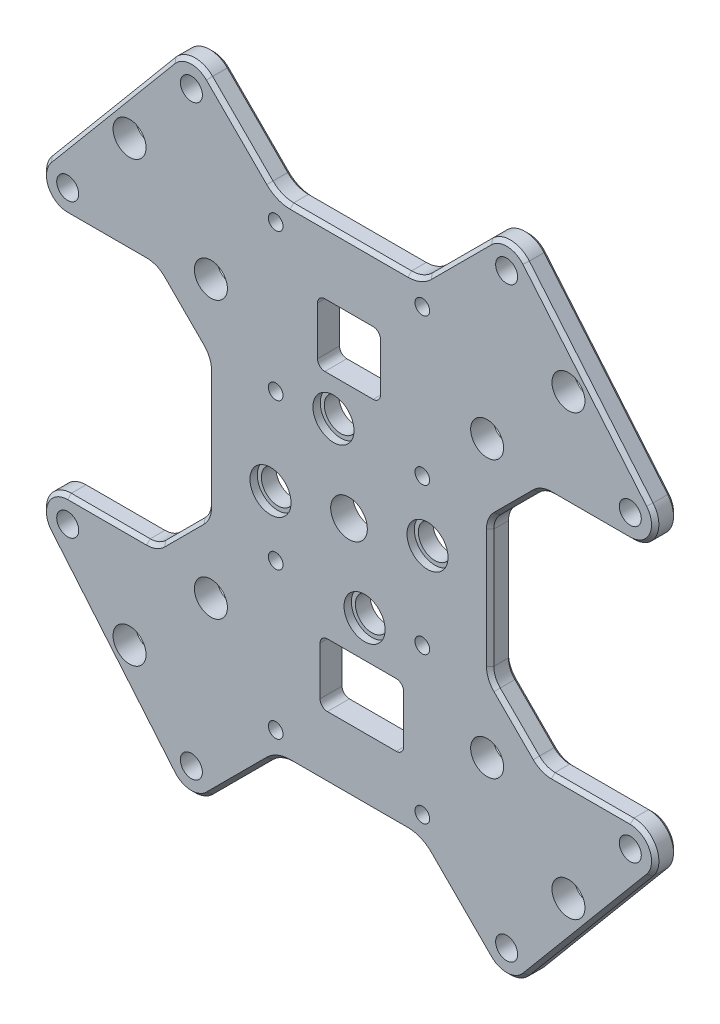
SolidWorks part; units mm, degrees
ref_plane "前视基准面" through (0, 0, 0) normal (0, 0, 1) x (1, 0, 0)
ref_plane "上视基准面" through (0, 0, 0) normal (0, 1, 0) x (1, 0, 0)
ref_plane "右视基准面" through (0, 0, 0) normal (1, 0, 0) x (0, 0, -1)
sketch "草图1" plane through (0, 0, 0) normal (0, 0, 1) x (1, 0, 0)
  line L0 (0, 0) -> (0, -25.4464) construction
  line L1 (0, 0) -> (25.4542, 0) construction
  line L22 (-19.0958, 42.4042) -> (-10.8632, 34.1716)
  line L23 (1.75, -20) -> (0, -20) construction
  line L24 (-14.5, -7) -> (18, -7) construction
  line L26 (-3.2929, 24.2929) -> (3.2929, 24.2929)
  line L27 (-4.2929, 23.2929) -> (-4.2929, 16.7071)
  line L28 (-15.25, 0.5) -> (15.25, 0.5) construction
  line L29 (-17.25, 2.5) -> (-17.25, 37.5) construction
  line L30 (-15.25, 39.5) -> (15.25, 39.5) construction
  line L31 (17.25, 2.5) -> (17.25, 37.5) construction
  line L32 (-15.5, -8) -> (-15.5, -32) construction
  line L33 (-17.25, 0.5) -> (17.25, 39.5) construction
  line L34 (-17.25, 39.5) -> (17.25, 0.5) construction
  line L35 (-10, 30) -> (10, 30) construction
  line L36 (-10, 30) -> (-10, 10) construction
  line L37 (-10, 10) -> (10, 10) construction
  line L38 (10, 30) -> (10, 10) construction
  line L39 (-10, 30) -> (10, 10) construction
  line L40 (-10, 10) -> (10, 30) construction
  line L41 (-8.0348, 33) -> (8.0348, 33)
  line L42 (-45.823, 52.8941) -> (-16.201, 23.2721) construction
  line L43 (-3.2929, 15.7071) -> (3.2929, 15.7071)
  line L44 (-14.5, -33) -> (18, -33) construction
  line L45 (19, -8) -> (19, -32) construction
  line L46 (-15.5, -7) -> (19, -33) construction
  line L47 (-15.5, -33) -> (19, -7) construction
  line L48 (-10, -30) -> (10, -30) construction
  line L49 (-10, -30) -> (-10, -10) construction
  line L50 (-10, -10) -> (10, -10) construction
  line L51 (10, -30) -> (10, -10) construction
  line L52 (-10, -30) -> (10, -10) construction
  line L53 (-10, -10) -> (10, -30) construction
  line L54 (-24.1062, 42.1835) -> (-40.9735, 22.0509)
  line L55 (-38.3673, 16.4673) -> (-27.6095, 16.4673)
  line L56 (-25.4882, 15.5887) -> (-20.1287, 10.2292)
  line L57 (-19.25, 8.1079) -> (-19.25, -8.1079)
  line L58 (-71.0072, 63.9361) -> (-82.5161, 75.445) construction
  line L59 (19.25, 8.1079) -> (19.25, -8.1079)
  line L60 (25.4882, 15.5887) -> (20.1287, 10.2292)
  line L61 (38.3673, 16.4673) -> (27.6095, 16.4673)
  line L62 (24.1062, 42.1835) -> (40.9735, 22.0509)
  line L63 (19.0958, 42.4042) -> (10.8632, 34.1716)
  line L64 (25.4882, -15.5887) -> (20.1287, -10.2292)
  line L65 (38.3673, -16.4673) -> (27.6095, -16.4673)
  line L66 (24.1062, -42.1835) -> (40.9735, -22.0509)
  line L67 (19.0958, -42.4042) -> (10.8632, -34.1716)
  line L68 (-8.0348, -33) -> (8.0348, -33)
  line L69 (-19.0958, -42.4042) -> (-10.8632, -34.1716)
  line L70 (-24.1062, -42.1835) -> (-40.9735, -22.0509)
  line L71 (-38.3673, -16.4673) -> (-27.6095, -16.4673)
  line L72 (-25.4882, -15.5887) -> (-20.1287, -10.2292)
  line L73 (4.2929, 23.2929) -> (4.2929, 16.7071)
  line L74 (-4.2929, 24.2929) -> (4.2929, 15.7071) construction
  line L75 (-4.2929, 15.7071) -> (4.2929, 24.2929) construction
  line L76 (-2.9463, -15.7071) -> (6.4463, -15.7071)
  line L77 (-3.9463, -16.7071) -> (-3.9463, -23.2929)
  line L78 (-2.9463, -24.2929) -> (6.4463, -24.2929)
  line L79 (7.4463, -16.7071) -> (7.4463, -23.2929)
  line L80 (-3.9463, -15.7071) -> (7.4463, -24.2929) construction
  line L81 (-3.9463, -24.2929) -> (7.4463, -15.7071) construction
  circle A4 centre (10, -10) radius 1 construction
  circle A5 centre (10, 10) radius 1 construction
  circle A6 centre (-10, 10) radius 1 construction
  arc A7 (-3.9463, -23.2929) -> (-2.9463, -24.2929) centre (-2.9463, -23.2929) ccw
  circle A8 centre (-10, -10) radius 1 construction
  arc A9 (6.4463, -24.2929) -> (7.4463, -23.2929) centre (6.4463, -23.2929) ccw
  arc A10 (-2.9463, -15.7071) -> (-3.9463, -16.7071) centre (-2.9463, -16.7071) ccw
  arc A11 (6.4463, -15.7071) -> (7.4463, -16.7071) centre (6.4463, -16.7071) cw
  circle A16 centre (10, -10) radius 1
  circle A17 centre (10, 10) radius 1
  circle A18 centre (-10, 10) radius 1
  circle A20 centre (-10, -10) radius 1
  arc A24 (-4.2929, 16.7071) -> (-3.2929, 15.7071) centre (-3.2929, 16.7071) ccw
  arc A25 (3.2929, 15.7071) -> (4.2929, 16.7071) centre (3.2929, 16.7071) ccw
  arc A26 (3.2929, 24.2929) -> (4.2929, 23.2929) centre (3.2929, 23.2929) cw
  arc A27 (-3.2929, 24.2929) -> (-4.2929, 23.2929) centre (-3.2929, 23.2929) ccw
  circle A42 centre (0, 0) radius 2.5
  arc A58 (-17.25, 37.5) -> (-15.25, 39.5) centre (-15.25, 37.5) cw construction
  arc A59 (-15.25, 0.5) -> (-17.25, 2.5) centre (-15.25, 2.5) cw construction
  arc A60 (15.25, 0.5) -> (17.25, 2.5) centre (15.25, 2.5) ccw construction
  circle A61 centre (-10, 30) radius 1
  circle A62 centre (10, 30) radius 1
  arc A63 (-14.5, -7) -> (-15.5, -8) centre (-14.5, -8) ccw construction
  arc A64 (-15.5, -32) -> (-14.5, -33) centre (-14.5, -32) ccw construction
  arc A65 (18, -33) -> (19, -32) centre (18, -32) ccw construction
  arc A66 (18, -7) -> (19, -8) centre (18, -8) cw construction
  circle A67 centre (10, -30) radius 1
  circle A68 centre (-10, -30) radius 1
  arc A69 (15.25, 39.5) -> (17.25, 37.5) centre (15.25, 37.5) cw construction
  circle A70 centre (-38.3673, -19.8673) radius 1.5 construction
  circle A71 centre (-29.9337, -29.9337) radius 1.5 construction
  circle A72 centre (-21.5, -40) radius 1.5 construction
  circle A73 centre (-38.3673, -19.8673) radius 1.5
  circle A74 centre (-29.9337, -29.9337) radius 1.5
  circle A75 centre (-21.5, -40) radius 1.5
  circle A80 centre (-10.7071, -2.1213) radius 1.5 construction
  circle A81 centre (2.1213, -10.7071) radius 1.5 construction
  circle A82 centre (10.7071, 2.1213) radius 1.5 construction
  circle A83 centre (-2.1213, 10.7071) radius 1.5 construction
  circle A84 centre (-29.9337, 29.9337) radius 1.5 construction
  circle A85 centre (-18.8388, 18.8388) radius 1.5 construction
  circle A86 centre (29.9337, 29.9337) radius 1.5 construction
  circle A87 centre (18.8388, 18.8388) radius 1.5 construction
  circle A88 centre (29.9337, -29.9337) radius 1.5 construction
  circle A89 centre (18.8388, -18.8388) radius 1.5 construction
  circle A90 centre (-18.8388, -18.8388) radius 1.5 construction
  circle A95 centre (-10.7071, -2.1213) radius 1.5
  circle A96 centre (2.1213, -10.7071) radius 1.5
  circle A97 centre (10.7071, 2.1213) radius 1.5
  circle A98 centre (-2.1213, 10.7071) radius 1.5
  circle A99 centre (-29.9337, 29.9337) radius 1.5
  circle A100 centre (-18.8388, 18.8388) radius 1.5
  circle A101 centre (29.9337, 29.9337) radius 1.5
  circle A102 centre (18.8388, 18.8388) radius 1.5
  circle A103 centre (29.9337, -29.9337) radius 1.5
  circle A104 centre (18.8388, -18.8388) radius 1.5
  circle A105 centre (-18.8388, -18.8388) radius 1.5
  circle A106 centre (-84.8528, -84.8528) radius 77.5 construction
  circle A107 centre (-21.5, 40) radius 1.5
  circle A108 centre (-29.9337, 29.9337) radius 1.5
  circle A109 centre (-38.3673, 19.8673) radius 1.5
  circle A110 centre (21.5, -40) radius 1.5
  circle A111 centre (29.9337, -29.9337) radius 1.5
  circle A112 centre (38.3673, -19.8673) radius 1.5
  circle A113 centre (38.3673, 19.8673) radius 1.5
  circle A114 centre (29.9337, 29.9337) radius 1.5
  circle A115 centre (21.5, 40) radius 1.5
  circle A116 centre (-21.5, 40) radius 3.4 construction
  circle A117 centre (-29.9337, 29.9337) radius 3.4 construction
  circle A118 centre (-38.3673, 19.8673) radius 3.4 construction
  arc A119 (-24.1062, 42.1835) -> (-19.0958, 42.4042) centre (-21.5, 40) cw
  arc A120 (-10.8632, 34.1716) -> (-8.0348, 33) centre (-8.0348, 37) ccw
  arc A121 (-40.9735, 22.0509) -> (-38.3673, 16.4673) centre (-38.3673, 19.8673) ccw
  arc A122 (-20.1287, 10.2292) -> (-19.25, 8.1079) centre (-22.25, 8.1079) cw
  arc A123 (-27.6095, 16.4673) -> (-25.4882, 15.5887) centre (-27.6095, 13.4673) cw
  arc A124 (20.1287, 10.2292) -> (19.25, 8.1079) centre (22.25, 8.1079) ccw
  arc A125 (27.6095, 16.4673) -> (25.4882, 15.5887) centre (27.6095, 13.4673) ccw
  arc A126 (40.9735, 22.0509) -> (38.3673, 16.4673) centre (38.3673, 19.8673) cw
  arc A127 (24.1062, 42.1835) -> (19.0958, 42.4042) centre (21.5, 40) ccw
  arc A128 (10.8632, 34.1716) -> (8.0348, 33) centre (8.0348, 37) cw
  arc A129 (20.1287, -10.2292) -> (19.25, -8.1079) centre (22.25, -8.1079) cw
  arc A130 (27.6095, -16.4673) -> (25.4882, -15.5887) centre (27.6095, -13.4673) cw
  arc A131 (40.9735, -22.0509) -> (38.3673, -16.4673) centre (38.3673, -19.8673) ccw
  arc A132 (24.1062, -42.1835) -> (19.0958, -42.4042) centre (21.5, -40) cw
  arc A133 (10.8632, -34.1716) -> (8.0348, -33) centre (8.0348, -37) ccw
  arc A134 (-10.8632, -34.1716) -> (-8.0348, -33) centre (-8.0348, -37) cw
  arc A135 (-24.1062, -42.1835) -> (-19.0958, -42.4042) centre (-21.5, -40) ccw
  arc A136 (-40.9735, -22.0509) -> (-38.3673, -16.4673) centre (-38.3673, -19.8673) cw
  arc A137 (-27.6095, -16.4673) -> (-25.4882, -15.5887) centre (-27.6095, -13.4673) ccw
  arc A138 (-20.1287, -10.2292) -> (-19.25, -8.1079) centre (-22.25, -8.1079) ccw
  point P7 (0, 20)
  point P45 (0, 20)
  point P99 (0, 20)
  point P111 (1.75, -20)
  point P126 (0, -20)
  point P177 (0, 33)
  point P178 (19.25, 0)
  point P203 (-19.25, 0)
  dimension "D1" = 5
  dimension "D2" = 2
  dimension "D3" = 34.5
  dimension "D4" = 39
  dimension "D8" = 1
  dimension "D5" = 155
  dimension "D6" = 6.8
  dimension "D7" = 4
  dimension "D14" = 3
  dimension "D18" = 1
  dimension "D9" = 9
  dimension "D10" = 3
  dimension "D11" = 5.5
  dimension "D12" = 3
  dimension "D13" = 2
  dimension "D15" = 7
  dimension "D16" = 5
  dimension "D17" = 5
extrude "凸台-拉伸1" add sketch "草图1" along normal blind 3 contours A138 L72 A137 L71 A136 L70 A135 L69 A134 L68 A133 L67 A132 L66 A131 L65 A130 L64 A129 L59 A124 L60 A125 L61 A126 L62 A127 L63 A128 L41 A120 L22 A119 L54 A121 L55 A123 L56 A122 L57 A115 A113 A110 A107 A105
chamfer "倒角1" distance 0.5 angle 45 80 edges at (41.4482, 18.4293, 0) (32.9884, 16.4673, 0) (32.5399, 32.1172, 0) (26.4614, 16.239, 0) (21.6496, 43.3967, 0) (22.8084, 12.9089, 0) (14.9795, 38.2879, 0) (19.4784, 9.2559, 0) (9.5656, 33.3045, 0) (19.25, 0, 0) (0, 33, 0) (19.4784, -9.2559, 0) (-9.5656, 33.3045, 0) (22.8084, -12.9089, 0) (-14.9795, 38.2879, 0) (26.4614, -16.239, 0) (-21.6496, 43.3967, 0) (32.9884, -16.4673, 0) (-32.5399, 32.1172, 0) (41.4482, -18.4293, 0) (-41.4482, 18.4293, 0) (32.5399, -32.1172, 0) (-32.9884, 16.4673, 0) (21.6496, -43.3967, 0) (-26.4614, 16.239, 0) (14.9795, -38.2879, 0) (-22.8084, 12.9089, 0) (9.5656, -33.3045, 0) (-19.4784, 9.2559, 0) (0, -33, 0) (-19.25, 0, 0) (-9.5656, -33.3045, 0) (-19.4784, -9.2559, 0) (-14.9795, -38.2879, 0) (-22.8084, -12.9089, 0) (-21.6496, -43.3967, 0) (-26.4614, -16.239, 0) (-32.5399, -32.1172, 0) (-32.9884, -16.4673, 0) (-41.4482, -18.4293, 0) (21.6496, 43.3967, 3) (14.9795, 38.2879, 3) (32.5399, 32.1172, 3) (9.5656, 33.3045, 3) (41.4482, 18.4293, 3) (0, 33, 3) (32.9884, 16.4673, 3) (-9.5656, 33.3045, 3) (26.4614, 16.239, 3) (-14.9795, 38.2879, 3) (22.8084, 12.9089, 3) (-21.6496, 43.3967, 3) (19.4784, 9.2559, 3) (-32.5399, 32.1172, 3) (19.25, 0, 3) (-41.4482, 18.4293, 3) (19.4784, -9.2559, 3) (-32.9884, 16.4673, 3) (22.8084, -12.9089, 3) (-26.4614, 16.239, 3) (26.4614, -16.239, 3) (-22.8084, 12.9089, 3) (32.9884, -16.4673, 3) (-19.4784, 9.2559, 3) (41.4482, -18.4293, 3) (-19.25, 0, 3) (32.5399, -32.1172, 3) (-19.4784, -9.2559, 3) (21.6496, -43.3967, 3) (-22.8084, -12.9089, 3) (14.9795, -38.2879, 3) (-26.4614, -16.239, 3) (9.5656, -33.3045, 3) (-32.9884, -16.4673, 3) (0, -33, 3) (-41.4482, -18.4293, 3) (-9.5656, -33.3045, 3) (-32.5399, -32.1172, 3) (-14.9795, -38.2879, 3) (-21.6496, -43.3967, 3)
sketch "草图3" plane through (0, 0, 3) normal (0, 0, 1) x (1, 0, 0)
  circle A4 centre (-2.1213, 10.7071) radius 2.25
  circle A5 centre (10.7071, 2.1213) radius 2.25
  circle A6 centre (2.1213, -10.7071) radius 2.25
  circle A7 centre (-10.7071, -2.1213) radius 2.25
  circle A8 centre (18.8388, 18.8388) radius 2.25
  circle A9 centre (29.9337, 29.9337) radius 2.25
  circle A10 centre (-29.9337, 29.9337) radius 2.25
  circle A11 centre (-18.8388, 18.8388) radius 2.25
  circle A12 centre (-18.8388, -18.8388) radius 2.25
  circle A13 centre (-29.9337, -29.9337) radius 2.25
  circle A14 centre (18.8388, -18.8388) radius 2.25
  circle A15 centre (29.9337, -29.9337) radius 2.25
  dimension "D1" = 4.5
extrude "切除-拉伸1" cut sketch "草图3" against normal blind 10
sketch "草图4" plane through (0, 0, 3) normal (0, 0, 1) x (1, 0, 0)
  circle A0 centre (-2.1213, 10.7071) radius 2.8
  circle A1 centre (10.7071, 2.1213) radius 2.8
  circle A2 centre (-10.7071, -2.1213) radius 2.8
  circle A3 centre (2.1213, -10.7071) radius 2.8
  dimension "D1" = 5.6
extrude "切除-拉伸2" cut sketch "草图4" against normal blind 1
